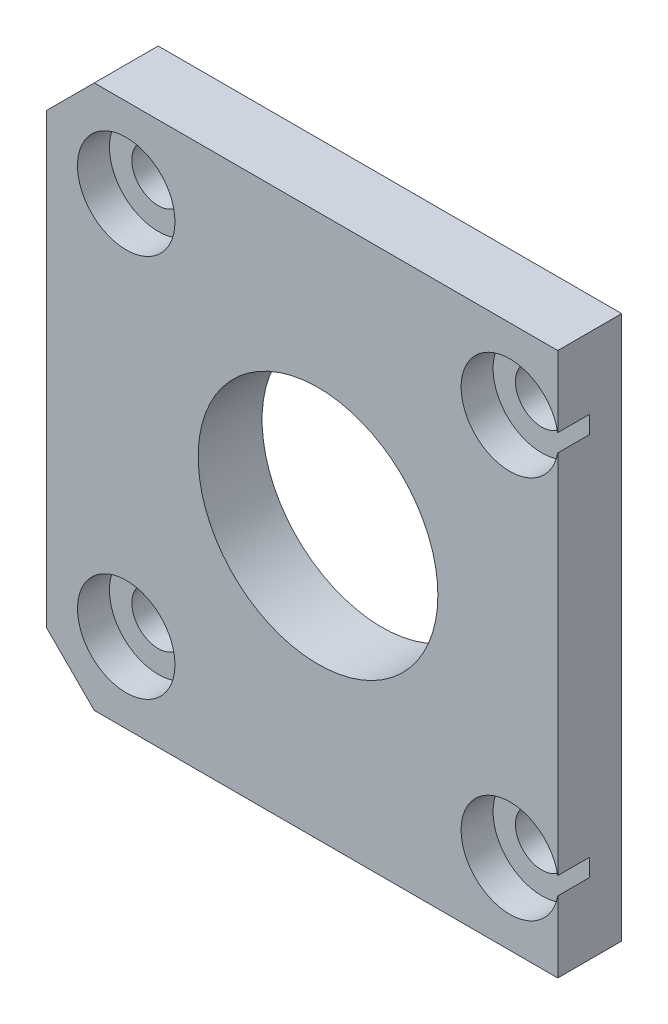
SolidWorks part; units mm, degrees
ref_plane "前视基准面" through (0, 0, 0) normal (0, 0, 1) x (1, 0, 0)
ref_plane "上视基准面" through (0, 0, 0) normal (0, 1, 0) x (1, 0, 0)
ref_plane "右视基准面" through (0, 0, 0) normal (1, 0, 0) x (0, 0, -1)
sketch "草图1" plane through (0, 0, 0) normal (0, 0, 1) x (1, 0, 0)
  line L0 (0, 31) -> (3, 34)
  line L1 (3, 0) -> (32, 0)
  line L2 (0, 3) -> (0, 31)
  line L3 (3, 34) -> (32, 34)
  line L4 (32, 0) -> (32, 34)
  line L5 (0, 3) -> (3, 0)
  circle A0 centre (17, 17) radius 7.5
  circle A1 centre (5, 29) radius 1.65
  circle A2 centre (29, 29) radius 1.65
  circle A3 centre (5, 5) radius 1.65
  circle A4 centre (29, 5) radius 1.65
  point P0 (0, 0)
  point P2 (0, 34)
  point P16 (0, 0)
  point P17 (0, 0)
  point P18 (0, 0)
  point P19 (0, 0)
  point P23 (4.5, 3.7592)
  point P24 (0, 17)
  dimension "D3" = 15
  dimension "D8" = 3.3
  dimension "D1" = 32
  dimension "D2" = 34
  dimension "D4" = 12
  dimension "D5" = 12
  dimension "D6" = 12
  dimension "D7" = 12
  dimension "D9" = 17
extrude "凸台-拉伸1" add sketch "草图1" along normal blind 4
sketch "草图2" plane through (0, 0, 4) normal (0, 0, 1) x (1, 0, 0)
  circle A0 centre (5, 29) radius 3.05
  circle A1 centre (29, 29) radius 3.05
  circle A2 centre (5, 5) radius 3.05
  circle A3 centre (29, 5) radius 3.05
  dimension "D1" = 6.1
extrude "切除-拉伸1" cut sketch "草图2" against normal blind 2
